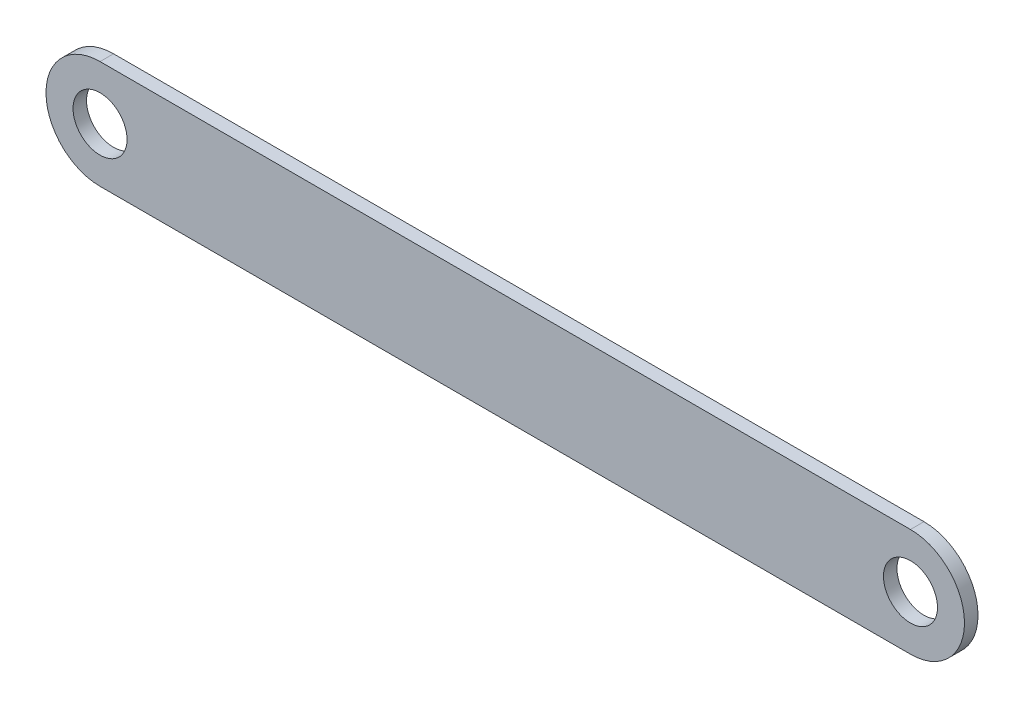
SolidWorks part; units mm, degrees
ref_plane "前视基准面" through (0, 0, 0) normal (0, 0, 1) x (1, 0, 0)
ref_plane "上视基准面" through (0, 0, 0) normal (0, 1, 0) x (1, 0, 0)
ref_plane "右视基准面" through (0, 0, 0) normal (1, 0, 0) x (0, 0, -1)
sketch "草图1" plane through (0, 0, 0) normal (0, 0, 1) x (1, 0, 0)
  line L0 (0, 0) -> (300, 0) construction
  line L1 (0, 20) -> (300, 20)
  line L2 (0, -20) -> (300, -20)
  arc A0 (0, 20) -> (0, -20) centre (0, 0) ccw
  arc A1 (300, -20) -> (300, 20) centre (300, 0) ccw
  circle A2 centre (0, 0) radius 10
  circle A3 centre (300, 0) radius 10
  point P3 (150, 0)
  dimension "D2" = 20
  dimension "D3" = 20
  dimension "D4" = 20
  dimension "D1" = 300
extrude "凸台-拉伸1" add sketch "草图1" along normal blind 5
